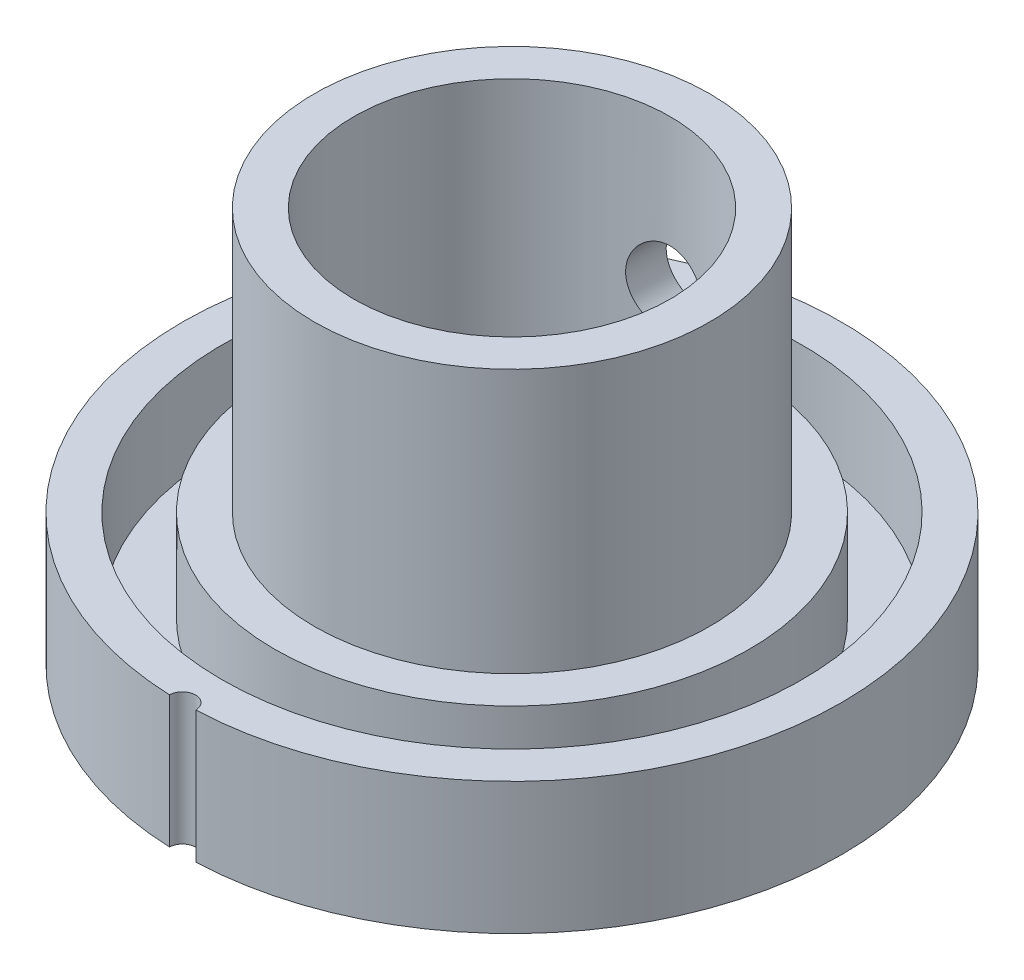
SolidWorks part; units mm, degrees
ref_plane "Front Plane" through (0, 0, 0) normal (0, 0, 1) x (1, 0, 0)
ref_plane "Top Plane" through (0, 0, 0) normal (0, 1, 0) x (1, 0, 0)
ref_plane "Right Plane" through (0, 0, 0) normal (1, 0, 0) x (0, 0, -1)
sketch "Sketch1" plane through (0, 0, 0) normal (0, 1, 0) x (1, 0, 0)
  circle A0 centre (0, 0) radius 12.5
  dimension "D1" = 25
extrude "Boss-Extrude1" add sketch "Sketch1" along normal blind 5
sketch "Sketch2" plane through (0, 5, 0) normal (0, 1, 0) x (1, 0, 0)
  circle A0 centre (0, 0) radius 7.5
  dimension "D1" = 15
extrude "Boss-Extrude2" add sketch "Sketch2" along normal blind 10
sketch "Sketch3" plane through (0, 0, 0) normal (0, 1, 0) x (1, 0, 0)
  line L1 (-7, -2) -> (7, -2)
  line L2 (-7, -2) -> (-7, 2)
  line L3 (-7, 2) -> (7, 2)
  line L4 (7, -2) -> (7, 2)
  line L5 (-7, -2) -> (7, 2) construction
  line L6 (-7, 2) -> (7, -2) construction
  point P0 (0, 0)
  dimension "D1" = 14
  dimension "D2" = 4
extrude "Boss-Extrude3" add sketch "Sketch3" along normal blind 10 draft 45 separate body
combine bodies "Combine1" operation type subtract main body 102 bodies to subtract 103
sketch "Sketch4" plane through (0, 0, 0) normal (0, -1, 0) x (1, 0, 0)
  line L0 (-7, 2) -> (7, 2) construction
  line L1 (-1, 2) -> (1, 2)
  line L2 (-1, 2) -> (-1, -2)
  line L3 (-1, -2) -> (1, -2)
  line L4 (1, 2) -> (1, -2)
  line L5 (7, -2) -> (-7, -2) construction
  point P4 (0, 2)
  dimension "D1" = 2
extrude "Boss-Extrude4" add sketch "Sketch4" against normal blind 0.8
sketch "Sketch5" plane through (0, 5, 0) normal (0, 1, 0) x (1, 0, 0)
  circle A8 centre (0, 0) radius 9
  circle A9 centre (0, 0) radius 9
  circle A11 centre (0, 0) radius 11
  circle A12 centre (0, 0) radius 11
  dimension "D1" = 1.5
  dimension "D2" = 1.5
extrude "Cut-Extrude1" cut sketch "Sketch5" against normal offset from surface (3.5 mm away) 1.5 up to face at (4, 0, 0)
sketch "Sketch6" plane through (0, 15, 0) normal (0, 1, 0) x (1, 0, 0)
  circle A2 centre (0, 0) radius 6
  circle A3 centre (0, 0) radius 6
  dimension "D1" = 1.5
extrude "Cut-Extrude2" cut sketch "Sketch6" against normal offset from surface (11.5 mm away) 3.5 up to face at (4, 0, 0)
sketch "Sketch7" plane through (0, 0, 0) normal (0, 0, 1) x (1, 0, 0)
  line L1 (12.5, 5) -> (-12.5, 5) construction
  circle A0 centre (0, 9.25) radius 1.5
  dimension "D1" = 3
  dimension "D2" = 4.25
extrude "Cut-Extrude3" cut sketch "Sketch7" against normal through all
sketch "Sketch8" plane through (0, 0, 0) normal (0, -1, 0) x (1, 0, 0)
  circle A0 centre (0, 12.5) radius 0.5
  circle A1 centre (0, 0) radius 12.5 construction
  dimension "D1" = 1
extrude "Cut-Extrude4" cut sketch "Sketch8" against normal up to next
